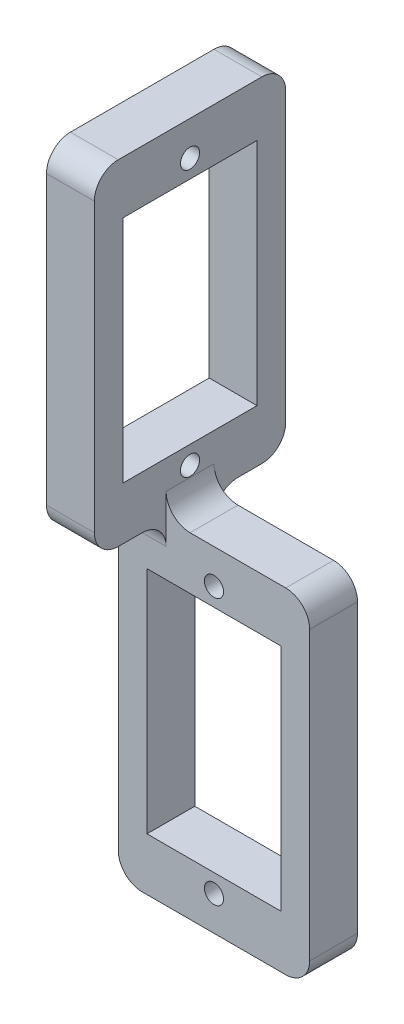
SolidWorks part; units mm, degrees
ref_plane "前视基准面" through (0, 0, 0) normal (0, 0, 1) x (1, 0, 0)
ref_plane "上视基准面" through (0, 0, 0) normal (0, 1, 0) x (1, 0, 0)
ref_plane "右视基准面" through (0, 0, 0) normal (1, 0, 0) x (0, 0, -1)
other "Configuration Table"
sketch "Sketch1" plane through (0, 0, 0) normal (0, 0, 1) x (1, 0, 0)
  line L1 (-7, -12) -> (7, -12)
  line L2 (-7, -12) -> (-7, 12)
  line L3 (-7, 12) -> (7, 12)
  line L4 (7, -12) -> (7, 12)
  line L5 (-7, -12) -> (7, 12) construction
  line L6 (-7, 12) -> (7, -12) construction
  line L7 (-10, -17.5) -> (10, -17.5)
  line L8 (-10, -17.5) -> (-10, 17.5)
  line L9 (-10, 17.5) -> (10, 17.5)
  line L10 (10, -17.5) -> (10, 17.5)
  line L11 (-10, -17.5) -> (10, 17.5) construction
  line L12 (-10, 17.5) -> (10, -17.5) construction
  point P0 (0, 0)
  point P6 (0, 0)
  dimension "D1" = 14
  dimension "D2" = 24
  dimension "D3" = 20
  dimension "D4" = 35
extrude "Boss-Extrude1" add sketch "Sketch1" along normal blind 5
sketch "Sketch2" plane through (0, 0, 5) normal (0, 0, 1) x (1, 0, 0)
  line L0 (0, 0) -> (0, 13.9) construction
  line L1 (0, 0) -> (5.3694, 0) construction
  circle A0 centre (0, 13.9) radius 1
  circle A1 centre (0, -13.9) radius 1
  dimension "D2" = 2
  dimension "D1" = 13.9
extrude "Cut-Extrude1" cut sketch "Sketch2" against normal blind 5
sketch "Sketch3" plane through (-10, 0, 0) normal (-1, 0, 0) x (0, 0, 1)
  line L0 (2.5, 17.5) -> (2.5, 30.9217) construction
  line L1 (5, 17.5) -> (0, 17.5) construction
  line L2 (-7.5, 17.5) -> (12.5, 17.5)
  line L3 (12.5, 17.5) -> (12.5, 52.5)
  line L4 (12.5, 52.5) -> (-7.5, 52.5)
  line L5 (2.5, 52.5) -> (2.5, 17.5)
  line L6 (-7.5, 17.5) -> (-7.5, 52.5)
  line M8 (5, 17.5) -> (0, 17.5)
  dimension "D1" = 35
  dimension "D2" = 10
extrude "Boss-Extrude2" add sketch "Sketch3" against normal blind 5 contours L6 L2 L5 L4 | L4 L5 L2 L3 M8
fillet "Fillet1" radius 2.5 2 edges at (-7.5, 17.5, 0) (-7.5, 17.5, 5)
sketch "Sketch5" plane through (-5, 0, 0) normal (1, 0, 0) x (0, 0, -1)
  line L0 (-12.5, 35) -> (7.5, 35) construction
  line L2 (-12.5, 17.5) -> (-12.5, 52.5) construction
  line L3 (7.5, 17.5) -> (7.5, 52.5) construction
  line L4 (-2.5, 52.5) -> (-2.5, 35) construction
  line L5 (-12.5, 52.5) -> (7.5, 52.5) construction
  line L6 (-2.5, 35) -> (-2.5, 21.1) construction
  line L7 (-9.5, 23) -> (4.5, 23)
  line L8 (-9.5, 23) -> (-9.5, 47)
  line L9 (-9.5, 47) -> (4.5, 47)
  line L10 (4.5, 23) -> (4.5, 47)
  line L11 (-9.5, 23) -> (4.5, 47) construction
  line L12 (-9.5, 47) -> (4.5, 23) construction
  circle A1 centre (-2.5, 21.1) radius 1
  circle A2 centre (-2.5, 48.9) radius 1
  dimension "D1" = 14
  dimension "D3" = 2
  dimension "D2" = 24
  dimension "D4" = 13.9
fillet "Fillet2" radius 2.5 7 edges at (-7.5, 17.5, 12.5) (-7.5, 17.5, -7.5) (-7.5, 52.5, -7.5) (-7.5, 52.5, 12.5) (10, -17.5, 2.5) (-10, -17.5, 2.5) (10, 17.5, 2.5)
extrude "Cut-Extrude2" cut sketch "Sketch5" against normal blind 10
